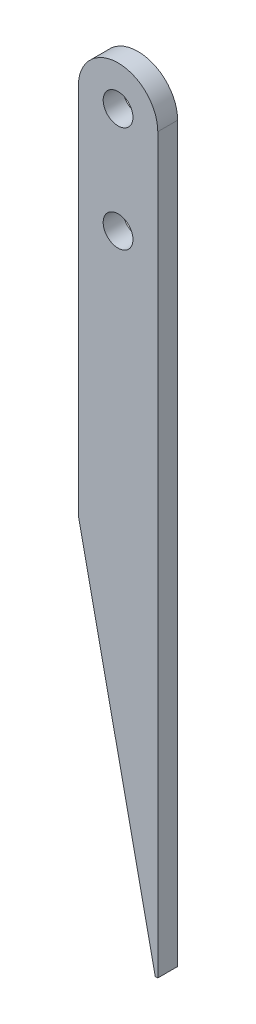
SolidWorks part; units mm, degrees
ref_plane "前视基准面" through (0, 0, 0) normal (0, 0, 1) x (1, 0, 0)
ref_plane "上视基准面" through (0, 0, 0) normal (0, 1, 0) x (1, 0, 0)
ref_plane "右视基准面" through (0, 0, 0) normal (1, 0, 0) x (0, 0, -1)
sketch "草图1" plane through (0, 0, 0) normal (0, 0, 1) x (1, 0, 0)
  line L0 (0, 0) -> (0, -10.66) construction
  line L1 (4, 0) -> (4, -75)
  line L2 (4, -75) -> (-4, -37.5)
  line L3 (-4, -37.5) -> (-4, 0)
  circle A0 centre (0, 0) radius 1.5
  circle A1 centre (0, -10.66) radius 1.5
  arc A2 (4, 0) -> (-4, 0) centre (0, 0) ccw
extrude "凸台-拉伸1" add sketch "草图1" along normal blind 2
sketch "草图2" plane through (0, 0, 2) normal (0, 0, 1) x (1, 0, 0)
  line L0 (4, -73.818) -> (3.7478, -73.818)
  line L1 (4, -75) -> (4, 0) construction
  line L2 (-4, -37.5) -> (4, -75) construction
  line L3 (3.7478, -73.818) -> (4, -75)
  line L4 (4, -75) -> (4, -73.818)
extrude "切除-拉伸1" cut sketch "草图2" against normal blind 2
